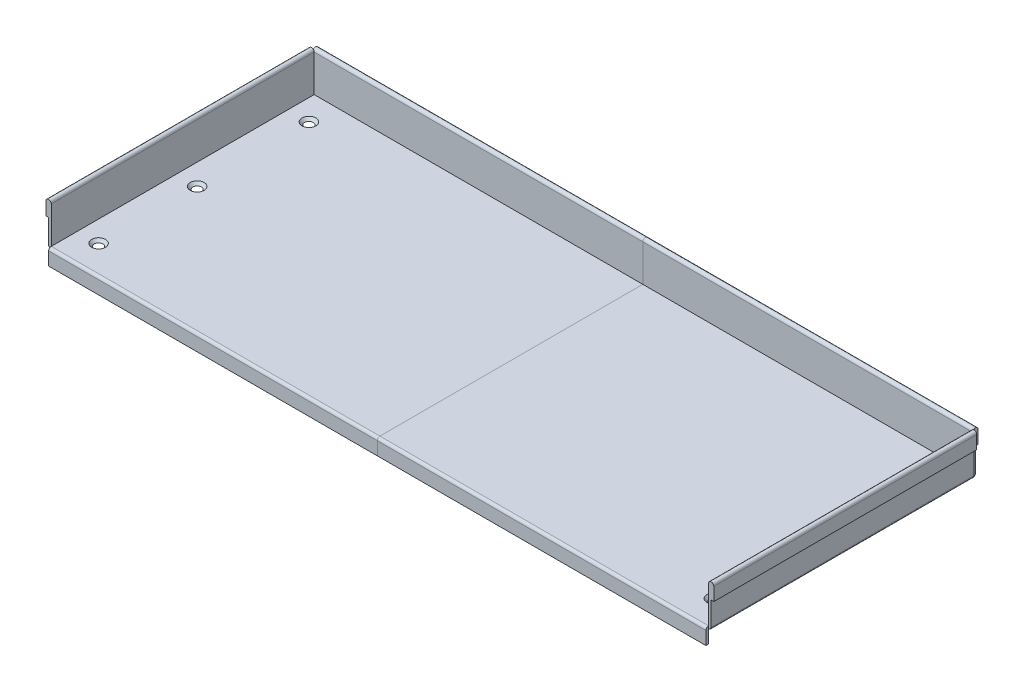
SolidWorks part; units mm, degrees
ref_plane "前基準面" through (0, 0, 0) normal (0, 0, 1) x (1, 0, 0)
ref_plane "上基準面" through (0, 0, 0) normal (0, 1, 0) x (1, 0, 0)
ref_plane "右基準面" through (0, 0, 0) normal (1, 0, 0) x (0, 0, -1)
ref_plane "平面1"
sketch "草圖1" plane through (0, 0, 0) normal (0, 0, 1) x (1, 0, 0)
  line L0 (0, 0) -> (0, -2)
  line L1 (0, -2) -> (250, -2)
  line L2 (252, 0) -> (252, 18)
  line L3 (252, 18) -> (254, 18)
  line L4 (254, 18) -> (254, 28)
  line L5 (250, 28) -> (250, 0)
  line L6 (250, 0) -> (0, 0)
  arc A0 (250, -2) -> (252, 0) centre (250, 0) ccw
  arc A1 (254, 28) -> (252, 30) centre (252, 28) ccw
  arc A2 (252, 30) -> (250, 28) centre (252, 28) ccw
extrude "擠出1" add sketch "草圖1" against normal blind 200
sketch "草圖2" plane through (0, 0, 0) normal (-1, 0, 0) x (0, 0, 1)
  line L0 (-200, -2) -> (-200, 28)
  line L1 (-204, 28) -> (-204, 18)
  line L2 (-204, 18) -> (-202, 18)
  line L3 (-202, 18) -> (-202, 0)
  arc A0 (-200, 28) -> (-202, 30) centre (-202, 28) ccw
  arc A1 (-202, 30) -> (-204, 28) centre (-202, 28) ccw
  arc A2 (-202, 0) -> (-200, -2) centre (-200, 0) ccw
extrude "擠出2" add sketch "草圖2" against normal blind 251
sketch "草圖3" plane through (0, 0, 0) normal (-1, 0, 0) x (0, 0, 1)
  line L0 (0, 0) -> (0, -12)
  line L1 (0, -12) -> (2, -12)
  line L2 (2, -12) -> (2, -2)
  arc A0 (2, -2) -> (0, 0) centre (0, -2) ccw
extrude "擠出3" add sketch "草圖3" against normal up to surface (250 mm away) up to face at (250, 14, -100)
ref_plane "平面2" through (234, 0, -200) normal (-1, 0, 0) x (0, 0, 1)
sketch "草圖4" plane through (234, 0, -200) normal (-1, 0, 0) x (0, 0, 1)
  line L0 (180, 0) -> (180, -2)
  line L1 (180, -2) -> (176.75, -2)
  line L2 (176.75, -2) -> (174.75, 0)
  line L3 (174.75, 0) -> (180, 0)
  line L4 (180, 0) -> (180, -2) construction
  line L5 (0, 0) -> (200, 0) construction
  line L6 (0, 28) -> (0, 0) construction
  dimension "D1" = 90
  dimension "D2" = 5.25
  dimension "D3" = 3.25
revolve "迴轉1" cut sketch "草圖4" angle 360 about L4
ref_plane "平面3" through (234, 0, -200) normal (-1, 0, 0) x (0, 0, 1)
sketch "草圖5" plane through (234, 0, -200) normal (-1, 0, 0) x (0, 0, 1)
  line L0 (20, 0) -> (20, -2)
  line L1 (20, -2) -> (16.75, -2)
  line L2 (16.75, -2) -> (14.75, 0)
  line L3 (14.75, 0) -> (20, 0)
  line L4 (20, 0) -> (20, -2) construction
  line L5 (0, 28) -> (0, 0) construction
  dimension "D1" = 20
  dimension "D2" = 183.25
  dimension "D3" = 185.25
revolve "迴轉2" cut sketch "草圖5" angle 360 about L4
ref_plane "平面4" through (234, 0, -200) normal (-1, 0, 0) x (0, 0, 1)
sketch "草圖6" plane through (234, 0, -200) normal (-1, 0, 0) x (0, 0, 1)
  line L0 (105, 0) -> (105, -2)
  line L1 (105, -2) -> (101.75, -2)
  line L2 (101.75, -2) -> (99.75, 0)
  line L3 (99.75, 0) -> (105, 0)
  line L4 (105, 0) -> (105, -2) construction
  line L5 (0, 0) -> (200, 0) construction
  line L6 (0, 28) -> (0, 0) construction
  dimension "D1" = 90
  dimension "D2" = 5.25
  dimension "D3" = 3.25
revolve "迴轉3" cut sketch "草圖6" angle 360 about L4
ref_plane "平面5" through (0, -1, -120) normal (-1, 0, 0) x (0, 1, 0)
mirror "鏡射1" about plane through (0, -1, -120) normal (-1, 0, 0) of bodies 105
